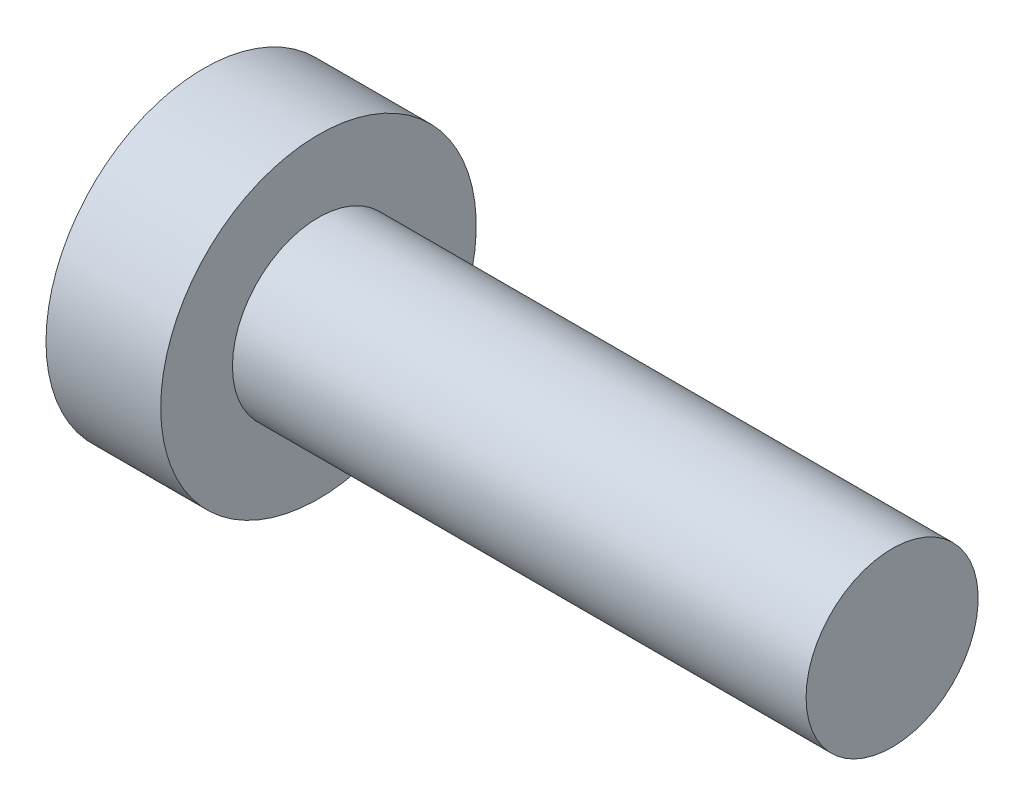
SolidWorks part; units mm, degrees
material "SCM435"
ref_plane "Front Plane" through (0, 0, 0) normal (0, 0, 1) x (1, 0, 0)
ref_plane "Top Plane" through (0, 0, 0) normal (0, 1, 0) x (1, 0, 0)
ref_plane "Right Plane" through (0, 0, 0) normal (1, 0, 0) x (0, 0, -1)
sketch "Sketch1" plane through (0, 0, 0) normal (0, 0, 1) x (1, 0, 0)
  line L0 (-2, 0) -> (-2, 2.75)
  line L1 (-2, 2.75) -> (0, 2.75)
  line L2 (0, 2.75) -> (0, 1.5)
  line L3 (0, 1.5) -> (10, 1.5)
  line L4 (10, 1.5) -> (10, 0)
  line L5 (-22.3581, 0) -> (50.8059, 0) construction
  line L6 (10, 0) -> (-2, 0)
  dimension "DK_s" = 5.5
  dimension "BL" = 10
  dimension "K_s" = 2
  dimension "DS_s" = 3
revolve "Revolve1" add sketch "Sketch1" angle 360 about L5
cosmetic thread "Thread1" parameters "TD_s"=2.459
sketch "Sketch2" plane through (0, 0, 0) normal (0, 1, 0) x (1, 0, 0)
  line L0 (0, -1.5) -> (0, 1.5) construction
  line L1 (0.2217, 0) -> (-1.3254, -2.6796) construction
  line L3 (-5.6736, 0) -> (11.128, 0) construction
  line L6 (-2, 1.25) -> (-2, 0)
  line L7 (-0.5, 1.25) -> (-2, 1.25)
  line L8 (0.2217, 0) -> (-0.5, 1.25)
  line L9 (-2, 0) -> (0.2217, 0)
  dimension "S_s" = 2.5
  dimension "T_s" = 1.5
  dimension "K_s" = 2
  dimension "FIX_2" = 120
  dimension "FIX_3" = 120
revolve "Cut-Revolve1" cut sketch "Sketch2" angle 360 about L3
sketch "Sketch3" plane through (-2, 0, 0) normal (-1, 0, 0) x (0, 0, 1)
  line L1 (0, 1.4434) -> (-1.25, 0.7217)
  line L2 (-1.25, 0.7217) -> (-1.25, -0.7217)
  line L3 (-1.25, -0.7217) -> (0, -1.4434)
  line L4 (0, -1.4434) -> (1.25, -0.7217)
  line L5 (1.25, -0.7217) -> (1.25, 0.7217)
  line L6 (1.25, 0.7217) -> (0, 1.4434)
  circle A0 centre (0, 0) radius 1.25 construction
  dimension "S_s" = 2.5
extrude "Cut-Extrude1" cut sketch "Sketch3" against normal blind 1.5
